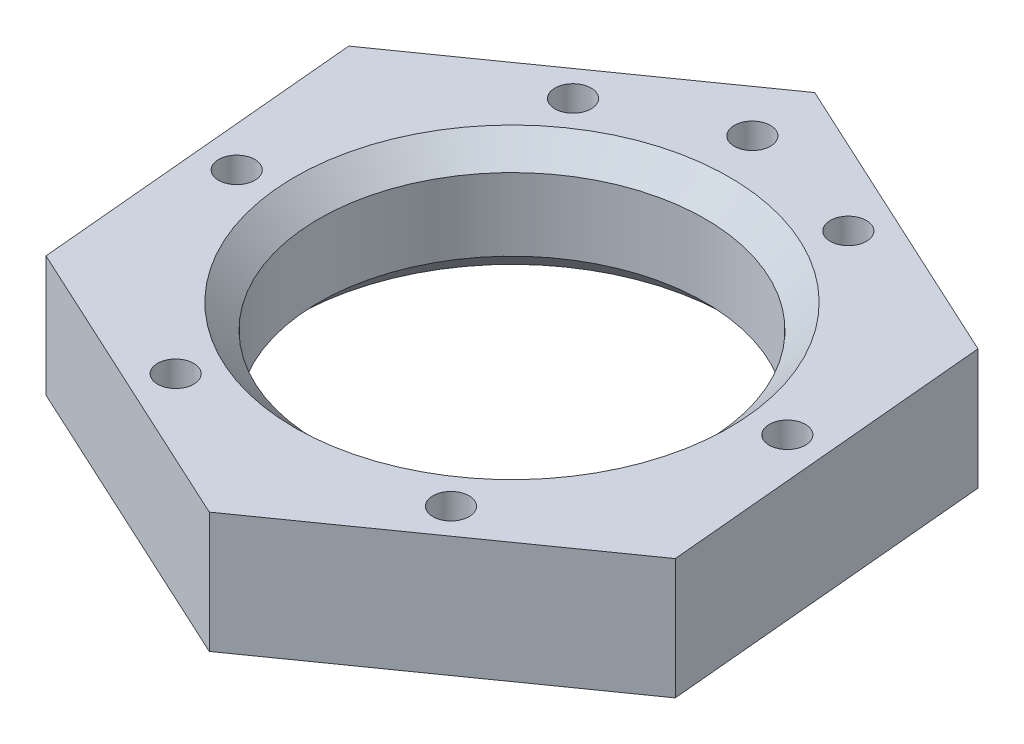
SolidWorks part; units mm, degrees
ref_plane "Front" through (0, 0, 0) normal (0, 0, 1) x (1, 0, 0)
ref_plane "Top" through (0, 0, 0) normal (0, 1, 0) x (1, 0, 0)
ref_plane "Right" through (0, 0, 0) normal (1, 0, 0) x (0, 0, -1)
sketch "Sketch1" plane through (0, 0, 0) normal (0, 1, 0) x (1, 0, 0)
  line L1 (1.5939, -17.5253) -> (15.9743, -7.3823)
  line L2 (15.9743, -7.3823) -> (14.3804, 10.143)
  line L3 (14.3804, 10.143) -> (-1.5939, 17.5253)
  line L4 (-1.5939, 17.5253) -> (-15.9743, 7.3823)
  line L5 (-15.9743, 7.3823) -> (-14.3804, -10.143)
  line L6 (-14.3804, -10.143) -> (1.5939, -17.5253)
  circle A0 centre (0, 0) radius 15.24 construction
  dimension "D1" = 30.48
extrude "Boss-Extrude1" add sketch "Sketch1" along normal blind 6.35
sketch "Sketch2" plane through (0, 6.35, 0) normal (0, 1, 0) x (1, 0, 0)
  circle A0 centre (0, 0) radius 10.16
  dimension "D1" = 20.32
extrude "Cut-Extrude1" cut sketch "Sketch2" against normal through all
chamfer "Chamfer1" distance 1.27 angle 45 2 edges at (0, 0, 10.16) (0, 6.35, 10.16)
sketch "Sketch4" plane through (0, 6.35, 0) normal (0, 1, 0) x (1, 0, 0)
  line L0 (0, 0) -> (-8.7841, 12.4538) construction
  line L1 (-1.5939, 17.5253) -> (-15.9743, 7.3823) construction
  line L3 (-1.5939, 17.5253) -> (0, 0) construction
  circle A0 centre (-7.6861, 10.8971) radius 0.9525
  circle A1 centre (5.5941, 12.1049) radius 0.9525
  circle A2 centre (13.2802, 1.2078) radius 0.9525
  circle A3 centre (7.6861, -10.8971) radius 0.9525
  circle A4 centre (-5.5941, -12.1049) radius 0.9525
  circle A5 centre (-1.2653, 13.9126) radius 0.9525
  circle A6 centre (-13.2802, -1.2078) radius 0.9525
  point P17 (0, 0)
  point P22 (0, 0)
  dimension "D1" = 1.905
  dimension "D4" = 1.905
  dimension "D5" = 13.97
  dimension "D2" = 13.335
  dimension "D3" = 6
extrude "Cut-Extrude2" cut sketch "Sketch4" against normal through all
